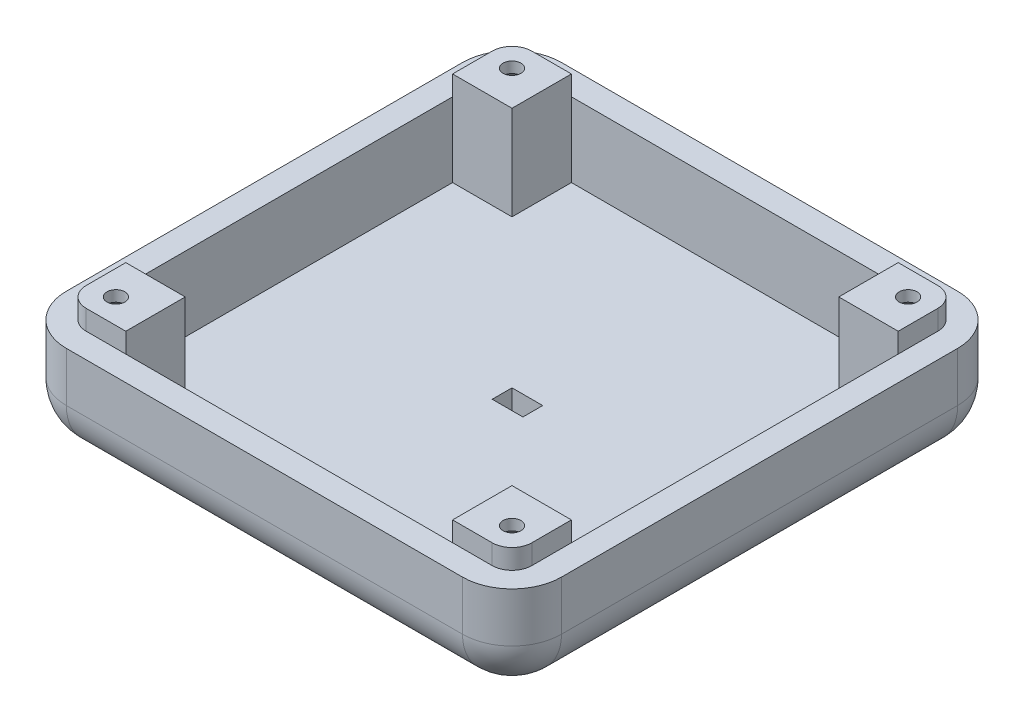
SolidWorks part; units mm, degrees
ref_plane "Front Plane" through (0, 0, 0) normal (0, 0, 1) x (1, 0, 0)
ref_plane "Top Plane" through (0, 0, 0) normal (0, 1, 0) x (1, 0, 0)
ref_plane "Right Plane" through (0, 0, 0) normal (1, 0, 0) x (0, 0, -1)
sketch "Sketch1" plane through (0, 0, 0) normal (0, 1, 0) x (1, 0, 0)
  line L1 (-25, 25) -> (25, 25)
  line L2 (-25, 25) -> (-25, -25)
  line L3 (-25, -25) -> (25, -25)
  line L4 (25, 25) -> (25, -25)
  line L5 (-25, 25) -> (25, -25) construction
  line L6 (-25, -25) -> (25, 25) construction
  point P0 (0, 0)
  dimension "D1" = 50
  dimension "D2" = 50
extrude "Boss-Extrude1" add sketch "Sketch1" along normal blind 10
shell "Shell1" thickness 2.5
fillet "Fillet1" radius 5 8 edges at (0, 0, 25) (-25, 5, 25) (-25, 5, -25) (-25, 0, 0) (0, 0, -25) (25, 5, -25) (25, 0, 0) (25, 5, 25)
sketch "Sketch2" plane through (0, 2.5, 0) normal (0, 1, 0) x (1, 0, 0)
  line L0 (22.5, 22.5) -> (16.5, 22.5)
  line L1 (-22.5, 22.5) -> (-16.5, 22.5)
  line L2 (-22.5, 22.5) -> (-22.5, 16.5)
  line L3 (-22.5, 16.5) -> (-16.5, 16.5)
  line L4 (-16.5, 22.5) -> (-16.5, 16.5)
  line L5 (22.5, 22.5) -> (22.5, 16.5)
  line L6 (22.5, 16.5) -> (16.5, 16.5)
  line L7 (16.5, 22.5) -> (16.5, 16.5)
  line L8 (22.5, -22.5) -> (22.5, -16.5)
  line L9 (22.5, -22.5) -> (16.5, -22.5)
  line L10 (16.5, -22.5) -> (16.5, -16.5)
  line L11 (22.5, -16.5) -> (16.5, -16.5)
  line L12 (-22.5, -22.5) -> (-16.5, -22.5)
  line L13 (-22.5, -22.5) -> (-22.5, -16.5)
  line L14 (-22.5, -16.5) -> (-16.5, -16.5)
  line L15 (-16.5, -22.5) -> (-16.5, -16.5)
  point P20 (0, 0)
  dimension "D1" = 6
  dimension "D2" = 6
  dimension "D3" = 4
extrude "Boss-Extrude2" add sketch "Sketch2" along normal blind 9.5
hole_wizard "CSK SLOT for M1.6 Countersunk Flat Head Screw1" positions "Sketch5" profile "Sketch6" size "M1.6" standard "ISO" slot yes end condition up to next
sketch "Sketch5" plane through (0, 0, 0) normal (0, -1, 0) x (-1, 0, 0)
  point P0 (-20, -20)
  point P3 (20, -20)
  point P6 (20, 20)
  point P9 (-20, 20)
sketch "Sketch6" plane through (20, 0, 20) normal (1, 0, 0) x (0, 0, -1)
  line L0 (0, 0) -> (0, 12)
  line L1 (0, 12) -> (0.9, 12)
  line L2 (0.9, 12) -> (0.9, 10.9)
  line L3 (0.9, 10.9) -> (1.8, 10)
  line L4 (1.8, 10) -> (1.8, 0)
  line L6 (1.8, 0) -> (0, 0)
  line L7 (-0.9, 10.9) -> (-1.8, 10) construction
  line L11 (0, -6.35) -> (0, 107.95) construction
  dimension "Thru Hole Dia." = 1.8
  dimension "Thru Hole Depth" = 12
  dimension "C'Sink Dia." = 3.6
  dimension "C'Sink Angle" = 90
  dimension "Head Clearance" = 10
sketch "Sketch7" plane through (0, 0, 0) normal (0, -1, 0) x (1, 0, 0)
  line L1 (-6, 15.5) -> (6, 15.5)
  line L2 (-6, 15.5) -> (-6, -7.5)
  line L3 (-6, -7.5) -> (6, -7.5)
  line L4 (6, 15.5) -> (6, -7.5)
  line L5 (-18.2, -20) -> (18.2, -20) construction
  point P8 (0, 20)
  dimension "D1" = 12
  dimension "D2" = 23
  dimension "D3" = 12.5
extrude "Boss-Extrude3" add sketch "Sketch7" along normal blind 6 contours L2 L1 L4 L3
sketch "Sketch8" plane through (0, 0, -7.5) normal (0, 0, -1) x (-1, 0, 0)
  line L0 (0, -6) -> (0, 0) construction
  line L1 (6, -6) -> (-6, -6) construction
  line L2 (6, -3) -> (4, -3)
  line L3 (-6, 0) -> (-4, 0)
  line L4 (-6, 0) -> (-6, -3)
  line L5 (-6, -3) -> (-4, -3)
  line L6 (-4, 0) -> (-4, -3)
  line L7 (4, 0) -> (4, -3)
  line L8 (6, 0) -> (4, 0)
  line L9 (6, 0) -> (6, -3)
  dimension "D1" = 3
  dimension "D2" = 2
extrude "Cut-Extrude1" cut sketch "Sketch8" against normal through all
fillet "Fillet2" radius 1 3 edges at (6, -4.5, -7.5) (-6, -4.5, -7.5) (0, -6, -7.5)
sketch "Sketch9" plane through (0, 0, -7.5) normal (0, 0, -1) x (-1, 0, 0)
  line L0 (-4, -3) -> (4, -3) construction
  line L2 (-2.17, -2.1) -> (2.17, -2.1)
  line L3 (-2.17, -2.1) -> (-2.17, -3.9)
  line L4 (-2.17, -3.9) -> (2.17, -3.9)
  line L5 (2.17, -2.1) -> (2.17, -3.9)
  line L6 (-2.17, -2.1) -> (2.17, -3.9) construction
  line L7 (-2.17, -3.9) -> (2.17, -2.1) construction
  point P4 (0, -3)
  point P6 (0, -3)
  dimension "D1" = 4.34
  dimension "D2" = 1.8
extrude "Cut-Extrude2" cut sketch "Sketch9" against normal blind 4.4
sketch "Sketch10" plane through (0, 0, -3.1) normal (0, 0, -1) x (-1, 0, 0)
  line L0 (-2.17, -3) -> (2.17, -3) construction
  line L1 (-2.17, -2.1) -> (-2.17, -3.9) construction
  line L2 (2.17, -3.9) -> (2.17, -2.1) construction
  line L4 (-1.55, -2.45) -> (1.55, -2.45)
  line L5 (-1.55, -2.45) -> (-1.55, -3.55)
  line L6 (-1.55, -3.55) -> (1.55, -3.55)
  line L7 (1.55, -2.45) -> (1.55, -3.55)
  line L8 (-1.55, -2.45) -> (1.55, -3.55) construction
  line L9 (-1.55, -3.55) -> (1.55, -2.45) construction
  point P6 (0, -3)
  point P8 (0, -3)
  dimension "D1" = 3.1
  dimension "D2" = 1.1
extrude "Cut-Extrude3" cut sketch "Sketch10" against normal blind 3.55
sketch "Sketch13" plane through (0, -2.45, 0) normal (0, -1, 0) x (1, 0, 0)
  line L0 (1.55, 0.45) -> (1.55, -3.1) construction
  line L1 (-1.55, 0.45) -> (1.55, 0.45)
  line L2 (-1.55, 0.45) -> (-1.55, -1.55)
  line L3 (-1.55, -1.55) -> (1.55, -1.55)
  line L4 (1.55, 0.45) -> (1.55, -1.55)
  dimension "D1" = 2
extrude "Cut-Extrude4" cut sketch "Sketch13" against normal up to next
fillet "Fillet3" radius 2 4 edges at (-22.5, 11, -22.5) (22.5, 11, -22.5) (22.5, 11, 22.5) (-22.5, 11, 22.5)
